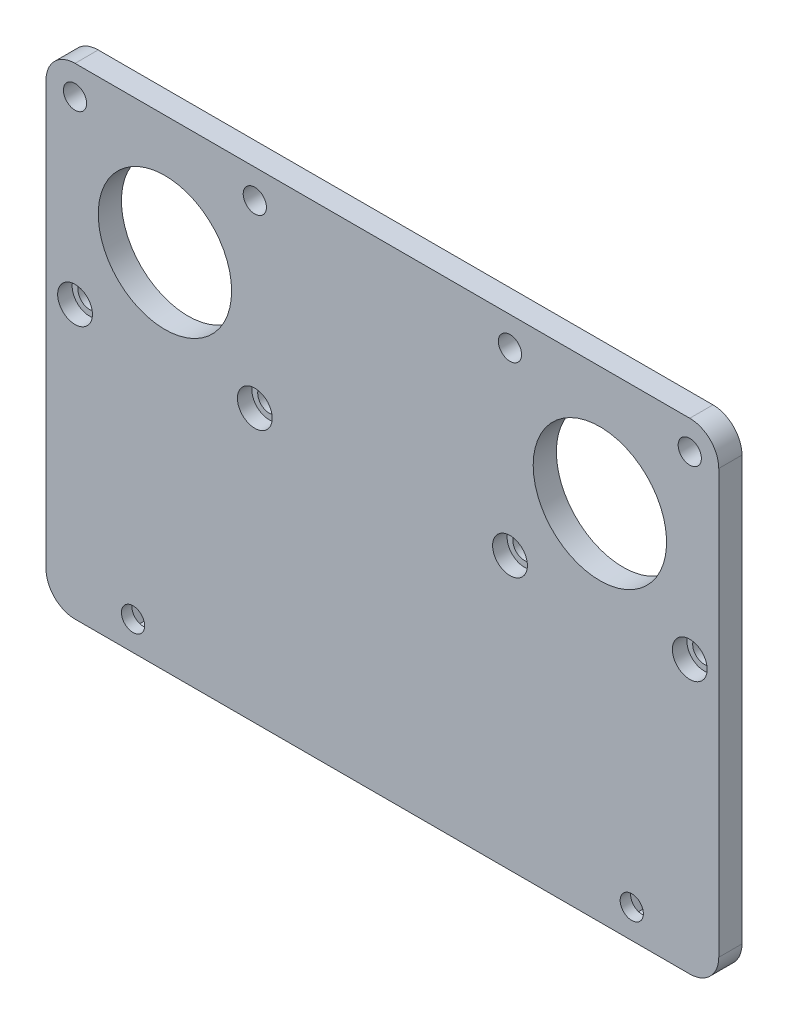
SolidWorks part; units mm, degrees
ref_plane "Plan de face" through (0, 0, 0) normal (0, 0, 1) x (1, 0, 0)
ref_plane "Plan de dessus" through (0, 0, 0) normal (0, 1, 0) x (1, 0, 0)
ref_plane "Plan de droite" through (0, 0, 0) normal (1, 0, 0) x (0, 0, -1)
sketch "Esquisse1" plane through (0, 0, 0) normal (0, 0, 1) x (1, 0, 0)
  line L1 (-57.0211, 49.8017) -> (58.9789, 49.8017)
  line L2 (-57.0211, 49.8017) -> (-57.0211, -33.1983)
  line L3 (-57.0211, -33.1983) -> (58.9789, -33.1983)
  line L4 (58.9789, 49.8017) -> (58.9789, -33.1983)
  dimension "D1" = 116
  dimension "D2" = 83
extrude "Boss.-Extru.1" add sketch "Esquisse1" along normal blind 4
fillet "Congé1" radius 5 4 edges at (58.9789, -33.1983, 2) (58.9789, 49.8017, 2) (-57.0211, 49.8017, 2) (-57.0211, -33.1983, 2)
sketch "Esquisse2" plane through (0, 0, 4) normal (0, 0, 1) x (1, 0, 0)
  line L0 (0.9789, -33.1983) -> (0.9789, 49.8017) construction
  line L1 (-52.0211, -33.1983) -> (53.9789, -33.1983) construction
  line L2 (53.9789, 49.8017) -> (-52.0211, 49.8017) construction
  line L3 (-57.0211, 44.8017) -> (-57.0211, -28.1983) construction
  line L4 (-52.0211, 44.8017) -> (-21.0211, 44.8017)
  line L5 (-52.0211, 44.8017) -> (-52.0211, 13.8017)
  line L6 (-52.0211, 13.8017) -> (-21.0211, 13.8017)
  line L7 (-21.0211, 44.8017) -> (-21.0211, 13.8017)
  line L8 (-52.0211, 44.8017) -> (-21.0211, 13.8017) construction
  line L9 (-52.0211, 13.8017) -> (-21.0211, 44.8017) construction
  circle A0 centre (-42.0211, -28.1983) radius 2
  circle A1 centre (-52.0211, 44.8017) radius 2
  circle A2 centre (-21.0211, 44.8017) radius 2
  circle A3 centre (-36.5211, 29.3017) radius 11.5
  circle A4 centre (-21.0211, 13.8017) radius 2
  circle A5 centre (-52.0211, 13.8017) radius 2
  circle A6 centre (43.9789, -28.1983) radius 2
  circle A7 centre (38.4789, 29.3017) radius 11.5
  circle A8 centre (22.9789, 13.8017) radius 2
  circle A9 centre (22.9789, 44.8017) radius 2
  circle A10 centre (53.9789, 44.8017) radius 2
  circle A11 centre (53.9789, 13.8017) radius 2
  point P6 (-36.5211, 29.3017)
  dimension "D1" = 4
  dimension "D8" = 23
  dimension "D2" = 20.5
  dimension "D3" = 5
  dimension "D4" = 15
  dimension "D5" = 31
  dimension "D6" = 31
  dimension "D7" = 20.5
extrude "Enlèv. mat.-Extru.1" cut sketch "Esquisse2" against normal blind 4 contours A3 | A5 | A1 | A2 | A4 | A0 | A9 | A10 | A7 | A8 | A11 | A6
sketch "Esquisse3" plane through (0, 0, 4) normal (0, 0, 1) x (1, 0, 0)
  circle A0 centre (-52.0211, 13.8017) radius 3
  circle A1 centre (-21.0211, 13.8017) radius 3
  circle A2 centre (22.9789, 13.8017) radius 3
  circle A3 centre (53.9789, 13.8017) radius 3
  dimension "D1" = 6
extrude "Enlèv. mat.-Extru.2" cut sketch "Esquisse3" against normal blind 2.5
sketch "Esquisse4" plane through (0, 0, 4) normal (0, 0, 1) x (1, 0, 0)
  line L0 (-52.0211, -33.1983) -> (53.9789, -33.1983) construction
  line L1 (-43.7531, -25.1983) -> (-45.4852, -28.1983)
  line L2 (-45.4852, -28.1983) -> (-43.7531, -31.1983)
  line L3 (-43.7531, -31.1983) -> (-40.289, -31.1983)
  line L4 (-40.289, -31.1983) -> (-38.557, -28.1983)
  line L5 (-38.557, -28.1983) -> (-40.289, -25.1983)
  line L6 (-40.289, -25.1983) -> (-43.7531, -25.1983)
  line L7 (42.2469, -25.1983) -> (40.5148, -28.1983)
  line L8 (40.5148, -28.1983) -> (42.2469, -31.1983)
  line L9 (42.2469, -31.1983) -> (45.711, -31.1983)
  line L10 (45.711, -31.1983) -> (47.443, -28.1983)
  line L11 (47.443, -28.1983) -> (45.711, -25.1983)
  line L12 (45.711, -25.1983) -> (42.2469, -25.1983)
  circle A0 centre (-42.0211, -28.1983) radius 3 construction
  circle A1 centre (43.9789, -28.1983) radius 3 construction
  dimension "D1" = 6
extrude "Enlèv. mat.-Extru.3" cut sketch "Esquisse4" along normal blind 2.2 from offset 4
